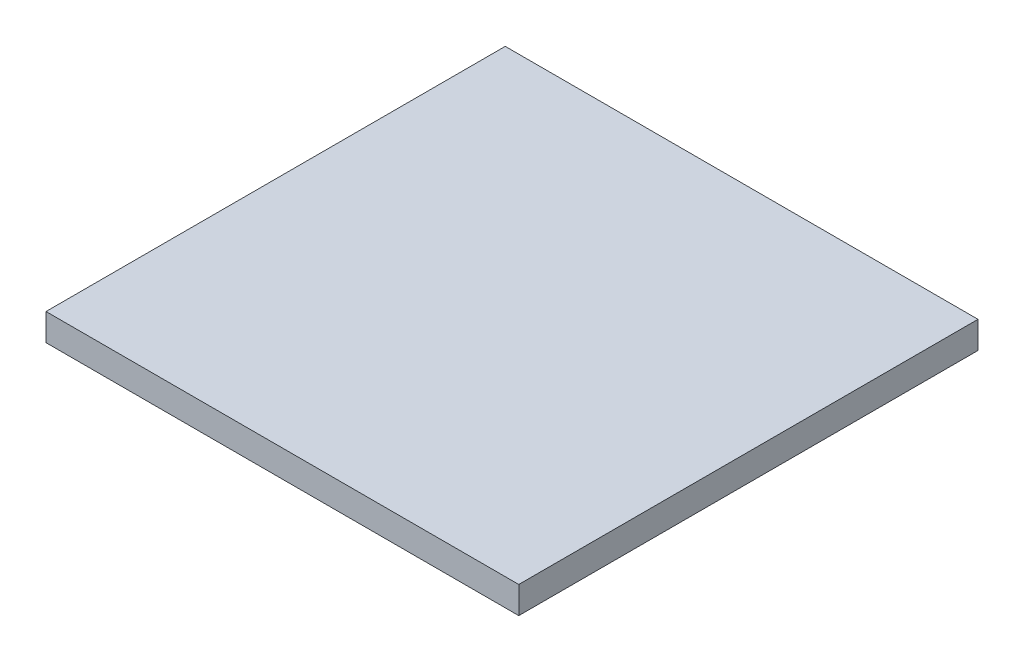
SolidWorks part; units mm, degrees
ref_plane "Front Plane" through (0, 0, 0) normal (0, 0, 1) x (1, 0, 0)
ref_plane "Top Plane" through (0, 0, 0) normal (0, 1, 0) x (1, 0, 0)
ref_plane "Right Plane" through (0, 0, 0) normal (1, 0, 0) x (0, 0, -1)
sketch "Sketch1" plane through (0, 0, 0) normal (0, 0, 1) x (1, 0, 0)
  line L1 (0, 0) -> (70, 0)
  line L2 (0, 0) -> (0, 4)
  line L3 (0, 4) -> (70, 4)
  line L4 (70, 0) -> (70, 4)
  dimension "D1" = 70
  dimension "D2" = 4
extrude "Profile" add sketch "Sketch1" along normal blind 68
equation "\"Profile_Depth\"= 68mm"
equation "\"D1@Profile\" = \"Profile_Depth\""
equation "\"Profile_Sketch_1\"= 70mm"
equation "\"D1@Sketch1\" = \"Profile_Sketch_1\""
equation "\"Profile_Sketch_2\"= 4mm"
equation "\"D2@Sketch1\" = \"Profile_Sketch_2\""
equation "\"EnvelopeWidth\"= 70mm"
equation "\"EnvelopeHeight\"= 4mm"
